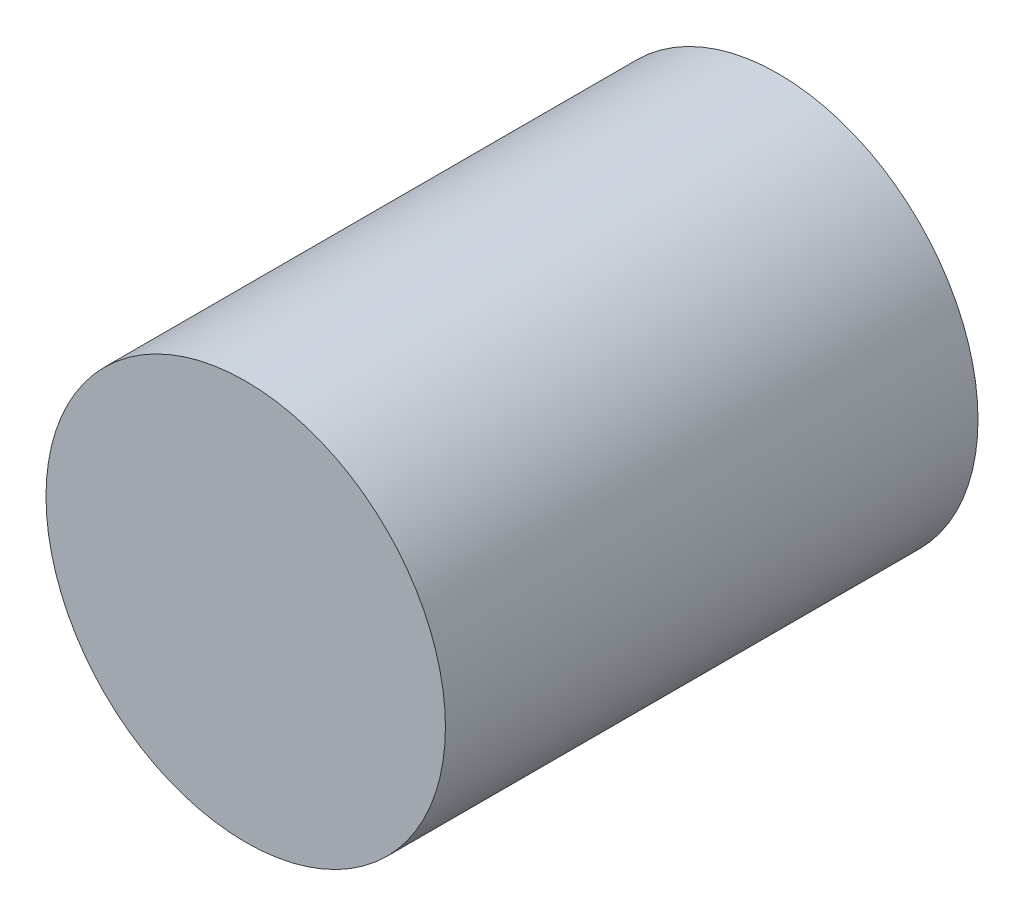
SolidWorks part; units mm, degrees
ref_plane "前视基准面" through (0, 0, 0) normal (0, 0, 1) x (1, 0, 0)
ref_plane "上视基准面" through (0, 0, 0) normal (0, 1, 0) x (1, 0, 0)
ref_plane "右视基准面" through (0, 0, 0) normal (1, 0, 0) x (0, 0, -1)
other "Configuration Table"
sketch "草图1" plane through (0, 0, 0) normal (0, 0, 1) x (1, 0, 0)
  circle A0 centre (0, 0) radius 7.5
  dimension "D1" = 15
extrude "凸台-拉伸1" add sketch "草图1" along normal mid plane 20
